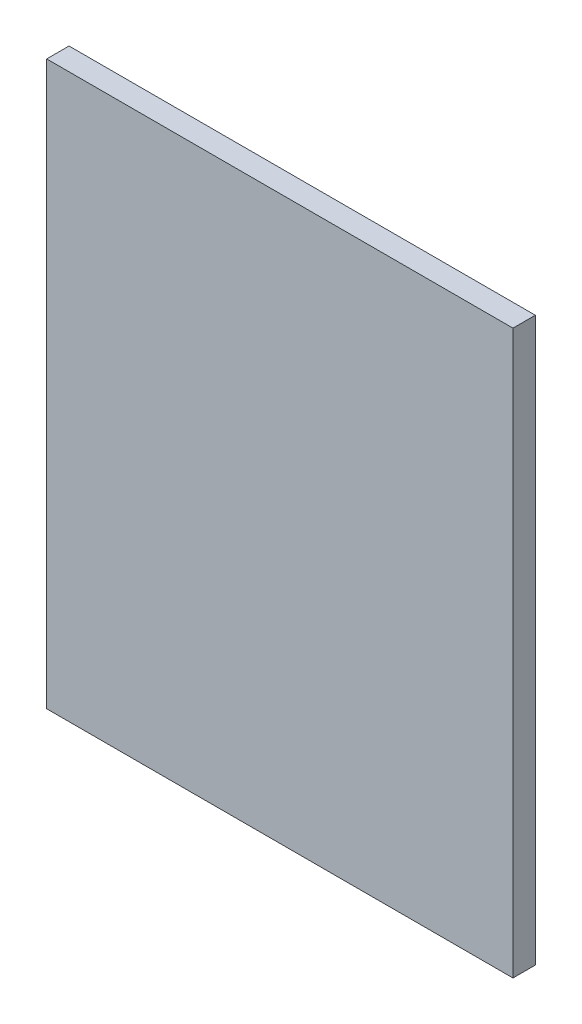
SolidWorks part; units mm, degrees
ref_plane "Front Plane" through (0, 0, 0) normal (0, 0, 1) x (1, 0, 0)
ref_plane "Top Plane" through (0, 0, 0) normal (0, 1, 0) x (1, 0, 0)
ref_plane "Right Plane" through (0, 0, 0) normal (1, 0, 0) x (0, 0, -1)
sketch "Sketch1" plane through (0, 0, 0) normal (0, 0, 1) x (1, 0, 0)
  line L1 (-30.0685, 22.4587) -> (32.5182, 22.4587)
  line L2 (-30.0685, 22.4587) -> (-30.0685, -53.0815)
  line L3 (-30.0685, -53.0815) -> (32.5182, -53.0815)
  line L4 (32.5182, 22.4587) -> (32.5182, -53.0815)
  dimension "D1" = 62.5867
  dimension "D2" = 75.5402
extrude "Boss-Extrude1" add sketch "Sketch1" along normal blind 3
